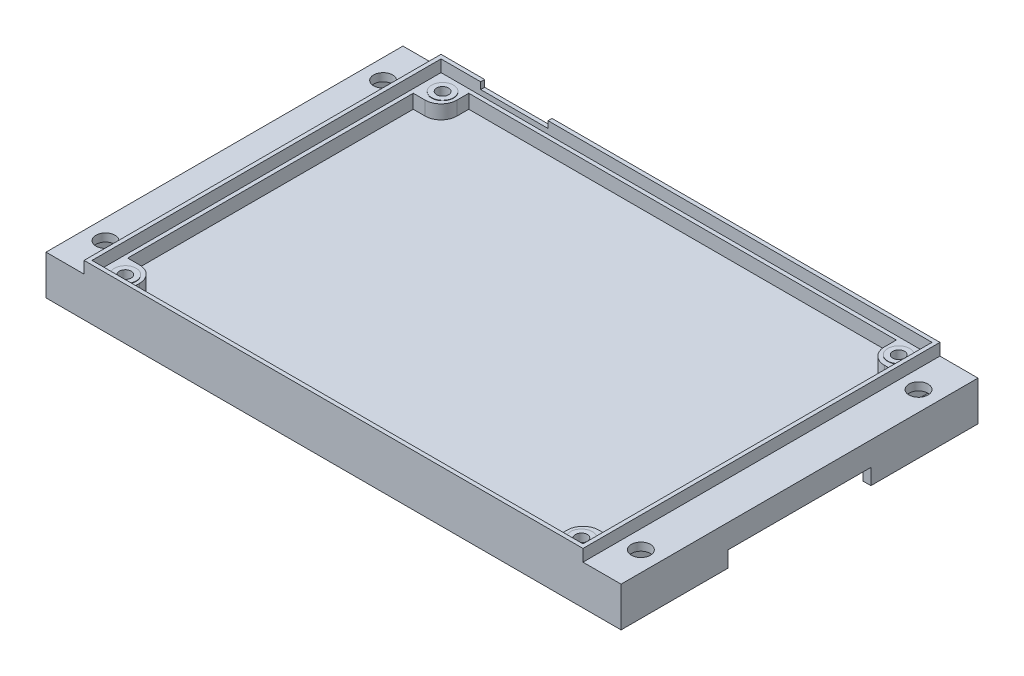
SolidWorks part; units mm, degrees
ref_plane "Спереди" through (0, 0, 0) normal (0, 0, 1) x (1, 0, 0)
ref_plane "Сверху" through (0, 0, 0) normal (0, 1, 0) x (1, 0, 0)
ref_plane "Справа" through (0, 0, 0) normal (1, 0, 0) x (0, 0, -1)
sketch "Эскиз1" plane through (0, 0, 0) normal (0, 1, 0) x (1, 0, 0)
  line L1 (72.5, -45) -> (-72.5, -45)
  line L2 (72.5, -45) -> (72.5, 45)
  line L3 (72.5, 45) -> (-72.5, 45)
  line L4 (-72.5, -45) -> (-72.5, 45)
  line L5 (72.5, -45) -> (-72.5, 45) construction
  line L6 (72.5, 45) -> (-72.5, -45) construction
  point P0 (0, 0)
  dimension "D1" = 145
  dimension "D2" = 90
extrude "Бобышка-Вытянуть1" add sketch "Эскиз1" along normal blind 10
sketch "Эскиз2" plane through (0, 10, 0) normal (0, 1, 0) x (1, 0, 0)
  line L0 (72.5, 45) -> (-72.5, 45) construction
  line L1 (62.9, -45) -> (-62.9, -45)
  line L2 (62.9, -45) -> (62.9, 45)
  line L3 (62.9, 45) -> (-62.9, 45)
  line L4 (-62.9, -45) -> (-62.9, 45)
  line L5 (62.9, -45) -> (-62.9, 45) construction
  line L6 (62.9, 45) -> (-62.9, -45) construction
  line L7 (72.5, -45) -> (72.5, 45) construction
  point P0 (0, 0)
  dimension "D1" = 0
  dimension "D2" = 9.6
extrude "Бобышка-Вытянуть2" add sketch "Эскиз2" along normal blind 3
sketch "Эскиз3" plane through (0, 13, 0) normal (0, 1, 0) x (1, 0, 0)
  line L0 (-62.9, 45) -> (-62.9, -45) construction
  line L1 (61.9, -44) -> (-61.9, -44)
  line L2 (61.9, -44) -> (61.9, 44)
  line L3 (61.9, 44) -> (-61.9, 44)
  line L4 (-61.9, -44) -> (-61.9, 44)
  line L5 (61.9, -44) -> (-61.9, 44) construction
  line L6 (61.9, 44) -> (-61.9, -44) construction
  line L7 (62.9, 45) -> (-62.9, 45) construction
  point P0 (0, 0)
  dimension "D1" = 1
  dimension "D2" = 1
extrude "Вырез-Вытянуть1" cut sketch "Эскиз3" against normal blind 3
sketch "Эскиз4" plane through (0, 10, 0) normal (0, 1, 0) x (1, 0, 0)
  line L0 (-53.9, 43) -> (53.9, 43)
  line L5 (53.9, 43) -> (53.9, 40)
  line L6 (57.9, 36) -> (60.9, 36)
  line L7 (60.9, 36) -> (60.9, -36)
  line L8 (60.9, -36) -> (57.9, -36)
  line L9 (53.9, -40) -> (53.9, -43)
  line L10 (53.9, -43) -> (-53.9, -43)
  line L11 (-53.9, -43) -> (-53.9, -40)
  line L12 (-57.9, -36) -> (-60.9, -36)
  line L13 (-60.9, -36) -> (-60.9, 36)
  line L14 (-60.9, 36) -> (-57.9, 36)
  line L15 (-53.9, 40) -> (-53.9, 43)
  line L19 (61.9, 44) -> (-61.9, 44) construction
  line L20 (-61.9, 44) -> (-61.9, -44) construction
  line L21 (61.9, -44) -> (61.9, 44) construction
  line L22 (-61.9, -44) -> (61.9, -44) construction
  line L23 (-61.9, 44) -> (-61.9, -44) construction
  line L24 (61.9, -44) -> (61.9, 44) construction
  line L25 (61.9, 44) -> (-61.9, 44) construction
  arc A3 (57.9, -36) -> (53.9, -40) centre (57.9, -40) ccw
  arc A4 (-53.9, -40) -> (-57.9, -36) centre (-57.9, -40) ccw
  arc A5 (53.9, 40) -> (57.9, 36) centre (57.9, 40) ccw
  arc A6 (-57.9, 36) -> (-53.9, 40) centre (-57.9, 40) ccw
  point P33 (-59.4, 36)
  dimension "D2" = 4
  dimension "D8" = 1
  dimension "D9" = 1
  dimension "D10" = 1
  dimension "D11" = 1
  dimension "D12" = 8
  dimension "D13" = 8
  dimension "D14" = 8
  dimension "D15" = 8
  dimension "D16" = 8
  dimension "D17" = 8
  dimension "D18" = 8
  dimension "D19" = 8
extrude "Вырез-Вытянуть2" cut sketch "Эскиз4" against normal blind 3.5
sketch "Эскиз6" plane through (0, 0, 0) normal (0, -1, 0) x (1, 0, 0)
  line L0 (-72.5, 45) -> (72.5, 45) construction
  line L1 (70.5, -43) -> (-70.5, -43)
  line L2 (70.5, -43) -> (70.5, 43)
  line L3 (70.5, 43) -> (-70.5, 43)
  line L4 (-70.5, -43) -> (-70.5, 43)
  line L5 (70.5, -43) -> (-70.5, 43) construction
  line L6 (70.5, 43) -> (-70.5, -43) construction
  line L7 (-72.5, -45) -> (-72.5, 45) construction
  point P0 (0, 0)
  dimension "D1" = 2
  dimension "D2" = 2
extrude "Вырез-Вытянуть3" cut sketch "Эскиз6" against normal blind 4
sketch "Эскиз7" plane through (72.5, 0, 0) normal (1, 0, 0) x (0, 0, -1)
  line L0 (-45, 0) -> (45, 0) construction
  line L1 (-18, 4) -> (18, 4)
  line L2 (-18, 4) -> (-18, -2)
  line L3 (-18, -2) -> (18, -2)
  line L4 (18, 4) -> (18, -2)
  dimension "D1" = 18
  dimension "D2" = 36
  dimension "D3" = 4
  dimension "D4" = 2
extrude "Вырез-Вытянуть4" cut sketch "Эскиз7" against normal through all
sketch "Эскиз8" plane through (0, 4, 0) normal (0, -1, 0) x (1, 0, 0)
  line L0 (-70.5, -43) -> (70.5, -43) construction
  line L1 (-70.5, 43) -> (-63.5, 43)
  line L2 (-70.5, 43) -> (-70.5, -43)
  line L3 (-70.5, -43) -> (-63.5, -43)
  line L4 (-63.5, 43) -> (-63.5, -43)
  line L6 (70.5, 43) -> (63.5, 43)
  line L7 (70.5, 43) -> (70.5, -43)
  line L8 (70.5, -43) -> (63.5, -43)
  line L9 (63.5, 43) -> (63.5, -43)
  dimension "D1" = 7
  dimension "D2" = 7
extrude "Вырез-Вытянуть5" cut sketch "Эскиз8" against normal blind 4
sketch "Эскиз14" plane through (0, 4, 0) normal (0, -1, 0) x (1, 0, 0)
  line L0 (-63.5, -37) -> (-63.5, -18)
  line L1 (-63.5, -43) -> (-63.5, 43) construction
  line L2 (-63.5, -18) -> (63.5, -18)
  line L3 (63.5, 43) -> (63.5, -43) construction
  line L4 (63.5, -18) -> (63.5, -37)
  line L5 (63.5, 43) -> (63.5, -43) construction
  line L6 (63.5, -37) -> (61.5, -37)
  line L7 (61.5, -37) -> (61.5, -20)
  line L8 (61.5, -20) -> (14.5, -20)
  line L9 (14.5, -20) -> (14.5, -43)
  line L10 (-63.5, -43) -> (63.5, -43) construction
  line L11 (14.5, -43) -> (12.5, -43)
  line L12 (12.5, -43) -> (12.5, -20)
  line L13 (12.5, -20) -> (-12.5, -20)
  line L14 (-12.5, -20) -> (-12.5, -43)
  line L15 (-70.5, -43) -> (70.5, -43) construction
  line L16 (-12.5, -43) -> (-14.5, -43)
  line L17 (-14.5, -43) -> (-14.5, -20)
  line L18 (-14.5, -20) -> (-61.5, -20)
  line L19 (-61.5, -20) -> (-61.5, -37)
  line L20 (-61.5, -37) -> (-63.5, -37)
  line L21 (-70.5, -18) -> (-72.5, -18) construction
  dimension "D1" = 6
  dimension "D2" = 6
  dimension "D3" = 0
  dimension "D4" = 2
  dimension "D5" = 2
  dimension "D6" = 2
  dimension "D7" = 2
  dimension "D8" = 2
  dimension "D9" = 2
  dimension "D10" = 2
  dimension "D11" = 25
  dimension "D12" = 47
  dimension "D13" = 47
extrude "Бобышка-Вытянуть6" add sketch "Эскиз14" along normal blind 4
sketch "Эскиз15" plane through (0, 4, 0) normal (0, -1, 0) x (1, 0, 0)
  line L0 (-61.5, 37) -> (-63.5, 37)
  line L1 (-63.5, -43) -> (-63.5, 43) construction
  line L2 (-63.5, 37) -> (-63.5, 18)
  line L3 (-63.5, 18) -> (-50.5, 18)
  line L4 (-50.5, 18) -> (-50.5, 43)
  line L5 (70.5, 43) -> (-70.5, 43) construction
  line L6 (-50.5, 43) -> (-55.5, 43)
  line L7 (-55.5, 43) -> (-55.5, 20)
  line L8 (-55.5, 20) -> (-61.5, 20)
  line L9 (-61.5, 20) -> (-61.5, 37)
  line L10 (63.5, 37) -> (63.5, 18)
  line L11 (63.5, 43) -> (63.5, -43) construction
  line L12 (63.5, 43) -> (63.5, -18) construction
  line L13 (63.5, 18) -> (50.5, 18)
  line L14 (50.5, 18) -> (50.5, 43)
  line L15 (63.5, 43) -> (-63.5, 43) construction
  line L16 (50.5, 43) -> (55.5, 43)
  line L17 (55.5, 43) -> (55.5, 20)
  line L18 (55.5, 20) -> (61.5, 20)
  line L19 (61.5, 20) -> (61.5, 37)
  line L20 (61.5, 37) -> (63.5, 37)
  line L21 (-13.5, 43) -> (-13.5, 18)
  line L22 (-13.5, 18) -> (13.5, 18)
  line L23 (13.5, 18) -> (13.5, 43)
  line L24 (13.5, 43) -> (8.5, 43)
  line L25 (8.5, 43) -> (8.5, 20)
  line L26 (8.5, 20) -> (-8.5, 20)
  line L27 (-8.5, 20) -> (-8.5, 43)
  line L28 (-8.5, 43) -> (-13.5, 43)
  line L29 (-72.5, 18) -> (-70.5, 18) construction
  line L30 (70.5, 18) -> (72.5, 18) construction
  line L31 (70.5, 18) -> (72.5, 18) construction
  dimension "D1" = 6
  dimension "D2" = 0
  dimension "D3" = 2
  dimension "D4" = 2
  dimension "D5" = 0
  dimension "D6" = 2
  dimension "D7" = 6
  dimension "D8" = 2
  dimension "D9" = 0
  dimension "D10" = 2
  dimension "D11" = 6
  dimension "D12" = 5
  dimension "D13" = 5
  dimension "D14" = 6
  dimension "D15" = 5
  dimension "D16" = 5
  dimension "D17" = 37
  dimension "D18" = 37
  dimension "D19" = 17
extrude "Бобышка-Вытянуть7" add sketch "Эскиз15" along normal blind 4
sketch "Эскиз16" plane through (0, 10, 0) normal (0, 1, 0) x (1, 0, 0)
  line L0 (-62.9, 45) -> (-62.9, -45) construction
  line L1 (62.9, 45) -> (-62.9, 45) construction
  line L2 (-62.9, -45) -> (62.9, -45) construction
  line L3 (62.9, -45) -> (62.9, 45) construction
  line L4 (62.9, -45) -> (62.9, 45) construction
  circle A0 centre (-57.5, 40) radius 2.75
  circle A1 centre (57.5, 40) radius 2.75
  circle A2 centre (-57.5, -40) radius 2.75
  circle A3 centre (57.5, -40) radius 2.75
  dimension "D3" = 5.5
  dimension "D6" = 5.5
  dimension "D10" = 5.5
  dimension "D13" = 5.5
  dimension "D1" = 5.4
  dimension "D2" = 5
  dimension "D4" = 5.4
  dimension "D5" = 5
  dimension "D7" = 80
  dimension "D8" = 5
  dimension "D9" = 5.4
  dimension "D11" = 5
  dimension "D12" = 5.4
extrude "Бобышка-Вытянуть8" add sketch "Эскиз16" along normal blind 0.1 and the other way blind 6.1
sketch "Эскиз17" plane through (0, 10.1, 0) normal (0, 1, 0) x (1, 0, 0)
  circle A0 centre (-57.5, 40) radius 1.5
  circle A1 centre (57.5, 40) radius 1.5
  circle A2 centre (-57.5, -40) radius 1.5
  circle A3 centre (57.5, -40) radius 1.5
  dimension "D1" = 3
  dimension "D2" = 3
  dimension "D3" = 3
  dimension "D4" = 3
extrude "Вырез-Вытянуть8" cut sketch "Эскиз17" against normal through all
sketch "Эскиз18" plane through (0, 10, 0) normal (0, 1, 0) x (1, 0, 0)
  line L0 (-72.5, 45) -> (-72.5, -45) construction
  line L1 (-72.5, -45) -> (-62.9, -45) construction
  line L2 (-62.9, 45) -> (-72.5, 45) construction
  line L3 (72.5, 45) -> (62.9, 45) construction
  line L4 (72.5, -45) -> (72.5, 45) construction
  line L5 (62.9, -45) -> (72.5, -45) construction
  circle A0 centre (-67.5, 35) radius 2.4
  circle A1 centre (-67.5, -35) radius 2.4
  circle A2 centre (67.5, 35) radius 2.4
  circle A3 centre (67.5, -35) radius 2.4
  dimension "D9" = 4.8
  dimension "D10" = 4.8
  dimension "D11" = 4.8
  dimension "D12" = 4.8
  dimension "D1" = 5
  dimension "D2" = 5
  dimension "D3" = 10
  dimension "D4" = 10
  dimension "D5" = 10
  dimension "D6" = 5
  dimension "D7" = 10
  dimension "D8" = 5
extrude "Вырез-Вытянуть9" cut sketch "Эскиз18" against normal through all
sketch "Эскиз19" plane through (0, 0, -45) normal (0, 0, -1) x (-1, 0, 0)
  line L0 (-62.9, 13) -> (62.9, 13) construction
  line L1 (34.9, 14) -> (51.9, 14)
  line L2 (34.9, 14) -> (34.9, 11.3)
  line L3 (34.9, 11.3) -> (51.9, 11.3)
  line L4 (51.9, 14) -> (51.9, 11.3)
  line L5 (62.9, 13) -> (62.9, 10) construction
  dimension "D1" = 1
  dimension "D2" = 11
  dimension "D3" = 28
  dimension "D4" = 1.7
extrude "Вырез-Вытянуть10" cut sketch "Эскиз19" against normal blind 3
